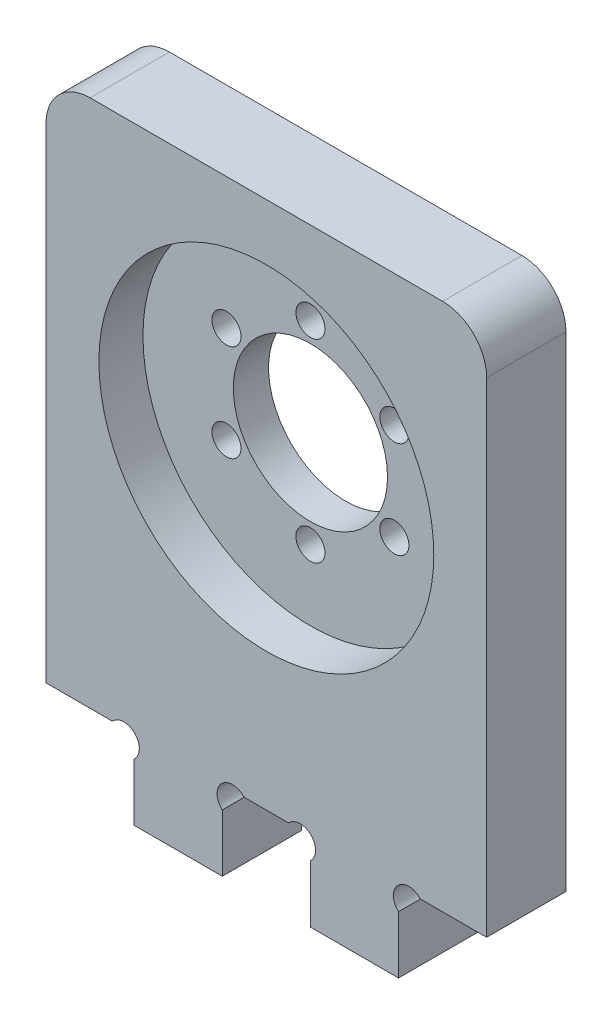
SolidWorks part; units mm, degrees
ref_plane "Plan de face" through (0, 0, 0) normal (0, 0, 1) x (1, 0, 0)
ref_plane "Plan de dessus" through (0, 0, 0) normal (0, 1, 0) x (1, 0, 0)
ref_plane "Plan de droite" through (0, 0, 0) normal (1, 0, 0) x (0, 0, -1)
sketch "Esquisse1" plane through (0, 0, 0) normal (0, 0, 1) x (1, 0, 0)
  line L1 (0, 0) -> (50, 0)
  line L2 (0, 0) -> (0, 60)
  line L3 (0, 60) -> (50, 60)
  line L4 (50, 0) -> (50, 60)
  dimension "D1" = 50
  dimension "D2" = 60
extrude "Boss.-Extru.1" add sketch "Esquisse1" along normal blind 9
sketch "Esquisse2" plane through (0, 0, 9) normal (0, 0, 1) x (1, 0, 0)
  line L0 (0, 0) -> (50, 0) construction
  line L1 (30, 0) -> (40, 0)
  line L2 (30, 0) -> (30, -9)
  line L3 (30, -9) -> (40, -9)
  line L4 (40, 0) -> (40, -9)
  line L5 (35, 0.8798) -> (35, -9) construction
  line L6 (25, 0) -> (25, -9) construction
  line L7 (15, 0.8798) -> (15, -9) construction
  line L8 (10, 0) -> (10, -9)
  line L9 (20, -9) -> (10, -9)
  line L10 (20, 0) -> (20, -9)
  line L11 (20, 0) -> (10, 0)
  dimension "D1" = 9
  dimension "D2" = 5
  dimension "D3" = 10
extrude "Boss.-Extru.2" add sketch "Esquisse2" against normal up to vertex (9 mm away)
sketch "Esquisse3" plane through (0, 0, 9) normal (0, 0, 1) x (1, 0, 0)
  line L0 (25, 60) -> (25, 34.6) construction
  line L1 (50, 60) -> (0, 60) construction
  line L2 (20, 0) -> (30, 0) construction
  circle A0 centre (25, 34.6) radius 8.75
  circle A1 centre (25, 45.6) radius 1.65
  circle A2 centre (34.5263, 40.1) radius 1.65
  circle A3 centre (34.5263, 29.1) radius 1.65
  circle A4 centre (25, 23.6) radius 1.65
  circle A5 centre (15.4737, 29.1) radius 1.65
  circle A6 centre (15.4737, 40.1) radius 1.65
  point P21 (25, 34.6)
  dimension "D1" = 17.5
  dimension "D3" = 11
  dimension "D4" = 3.3
  dimension "D2" = 34.6
  dimension "D5" = 6
extrude "Enlèv. mat.-Extru.1" cut sketch "Esquisse3" against normal up to vertex (9 mm away)
sketch "Esquisse4" plane through (0, 0, 9) normal (0, 0, 1) x (1, 0, 0)
  circle A0 centre (25, 34.6) radius 19
  dimension "D1" = 38
extrude "Enlèv. mat.-Extru.2" cut sketch "Esquisse4" against normal blind 5
fillet "Congé1" radius 5 2 edges at (50, 60, 4.5) (0, 60, 4.5)
sketch "Esquisse5" plane through (0, 0, 9) normal (0, 0, 1) x (1, 0, 0)
  line L0 (25, 0) -> (25, -8.4272) construction
  line L1 (20, 0) -> (30, 0) construction
  line L2 (30, 0) -> (30, -9) construction
  line L3 (27.5251, 0) -> (30, -2.4749)
  line L4 (28.7626, -1.2374) -> (28.8314, -1.1686) construction
  line L5 (28.8314, -1.1686) -> (30, 0) construction
  line L6 (30, 0) -> (30.0707, 0.0707) construction
  line L7 (20, 0) -> (19.9293, 0.0707) construction
  line L8 (21.1686, -1.1686) -> (20, 0) construction
  line L9 (21.2374, -1.2374) -> (21.1686, -1.1686) construction
  line L10 (22.4749, 0) -> (20, -2.4749)
  line L11 (35, -9) -> (35, -3.156) construction
  line L12 (30, -9) -> (40, -9) construction
  line L13 (40, 0) -> (39.9293, 0.0707) construction
  line L14 (41.1686, -1.1686) -> (40, 0) construction
  line L15 (41.2374, -1.2374) -> (41.1686, -1.1686) construction
  line L16 (42.4749, 0) -> (40, -2.4749)
  line L17 (30, 0) -> (30.0707, 0.0707) construction
  line L18 (8.7626, -1.2374) -> (8.8314, -1.1686) construction
  line L19 (8.8314, -1.1686) -> (10, 0) construction
  line L20 (10, 0) -> (10.0707, 0.0707) construction
  line L21 (7.5251, 0) -> (10, -2.4749)
  arc A0 (27.5251, 0) -> (30, -2.4749) centre (28.8314, -1.1686) cw
  arc A1 (22.4749, 0) -> (20, -2.4749) centre (21.1686, -1.1686) ccw
  arc A2 (42.4749, 0) -> (40, -2.4749) centre (41.1686, -1.1686) ccw
  arc A3 (7.5251, 0) -> (10, -2.4749) centre (8.8314, -1.1686) cw
  dimension "D1" = 3.5
  dimension "D2" = 0.1
extrude "Enlèv. mat.-Extru.3" cut sketch "Esquisse5" against normal through all both and the other way through all
